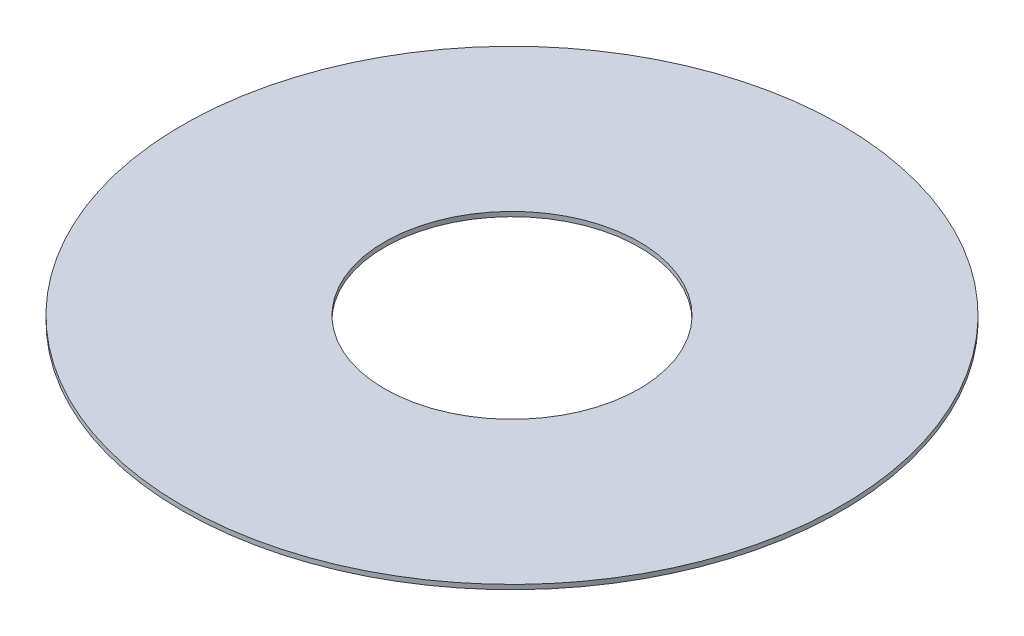
SolidWorks part; units mm, degrees
ref_plane "Front Plane" through (0, 0, 0) normal (0, 0, 1) x (1, 0, 0)
ref_plane "Top Plane" through (0, 0, 0) normal (0, 1, 0) x (1, 0, 0)
ref_plane "Right Plane" through (0, 0, 0) normal (1, 0, 0) x (0, 0, -1)
sketch "Sketch1" plane through (0, 0, 0) normal (0, 1, 0) x (1, 0, 0)
  circle A0 centre (0, 0) radius 32.8676
  circle A1 centre (0, 0) radius 12.7
  dimension "D1" = 65.7352
  dimension "D2" = 25.4
extrude "Boss-Extrude1" add sketch "Sketch1" along normal blind 0.4572
